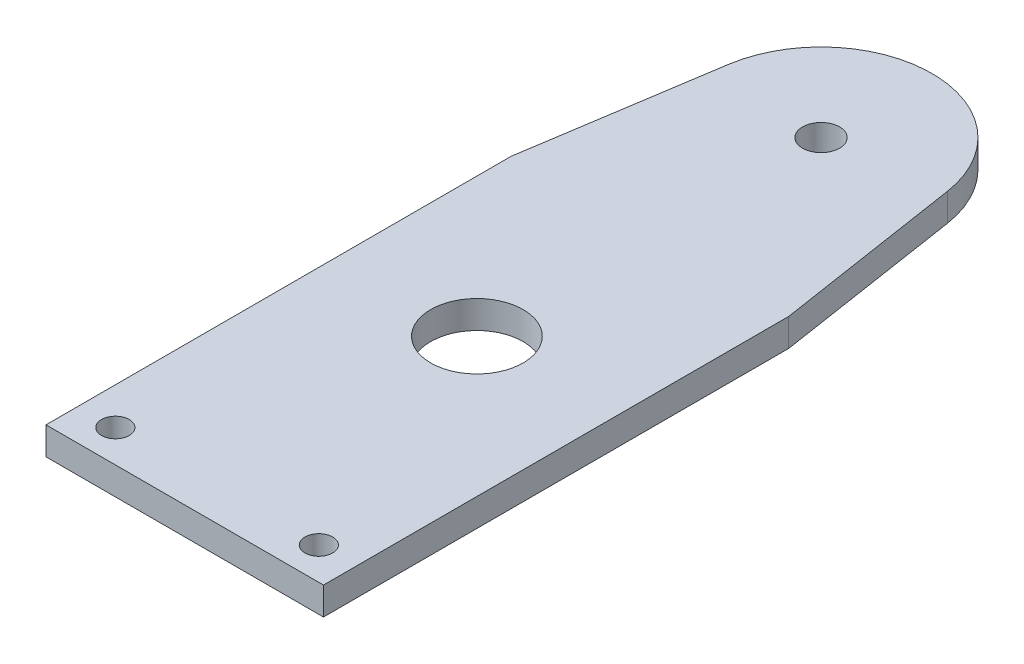
SolidWorks part; units mm, degrees
ref_plane "Спереди" through (0, 0, 0) normal (0, 0, 1) x (1, 0, 0)
ref_plane "Сверху" through (0, 0, 0) normal (0, 1, 0) x (1, 0, 0)
ref_plane "Справа" through (0, 0, 0) normal (1, 0, 0) x (0, 0, -1)
sketch "Эскиз1" plane through (0, 0, 0) normal (0, 1, 0) x (1, 0, 0)
  line L0 (-17.6252, -26.1173) -> (12.3748, -26.1173) construction
  line L1 (-17.6252, -29.6173) -> (12.3748, -29.6173) construction
  line L2 (-17.6252, -29.6173) -> (-17.6252, 48.1827) construction
  line L3 (-17.6252, 52.3827) -> (12.3748, 52.3827) construction
  line L4 (5.3748, -19.6173) -> (5.3748, -29.6173) construction
  line L5 (-13.6252, -27.6173) -> (8.3748, -27.6173) construction
  line L6 (-2.6252, -29.6173) -> (-2.6252, 60.301) construction
  line L7 (12.3748, -29.6173) -> (12.3748, 20.6827)
  line L8 (12.3748, 20.6827) -> (9.2341, 41.0146)
  line L9 (5.3748, -19.6173) -> (-10.6252, -19.6173) construction
  line L10 (5.3748, -29.6173) -> (12.3748, -29.6173)
  line L11 (-10.6252, -19.6173) -> (-10.6252, -29.6173) construction
  line L12 (-10.6252, -29.6173) -> (-17.6252, -29.6173)
  line L13 (-10.6252, -29.6173) -> (5.3748, -29.6173)
  line L14 (-17.6252, -29.6173) -> (-17.6252, 20.6827)
  line L15 (-17.6252, 20.6827) -> (-14.4846, 41.0146)
  circle A0 centre (-13.6252, -26.1173) radius 1.5
  circle A1 centre (8.3748, -26.1173) radius 1.5
  circle A2 centre (-2.6252, 39.1827) radius 2
  arc A3 (9.2341, 41.0146) -> (-14.4846, 41.0146) centre (-2.6252, 39.1827) ccw
  circle A4 centre (-2.6252, 1.9727) radius 5
  point P23 (-2.6252, -19.6173)
  dimension "D3" = 68.8
  dimension "D4" = 4
  dimension "D7" = 3
  dimension "D8" = 7
  dimension "D1" = 3.5
  dimension "D10" = 37.21
  dimension "D11" = 10
  dimension "D12" = 12
  dimension "D2" = 30
  dimension "D5" = 22
  dimension "D6" = 4
  dimension "D9" = 10
  dimension "D13" = 50.3
extrude "Бобышка-Вытянуть1" add sketch "Эскиз1" along normal blind 3
